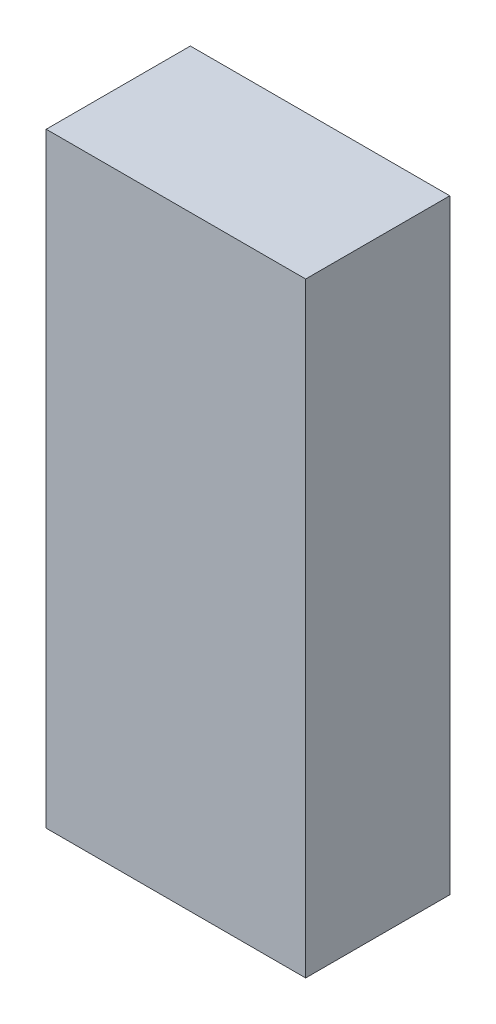
SolidWorks part; units mm, degrees
material "Copper"
ref_plane "Front Plane" through (0, 0, 0) normal (0, 0, 1) x (1, 0, 0)
ref_plane "Top Plane" through (0, 0, 0) normal (0, 1, 0) x (1, 0, 0)
ref_plane "Right Plane" through (0, 0, 0) normal (1, 0, 0) x (0, 0, -1)
sketch "Sketch1" plane through (0, 0, 0) normal (0, 0, 1) x (1, 0, 0)
  line L1 (-0.225, 0.525) -> (0.225, 0.525)
  line L2 (-0.225, 0.525) -> (-0.225, -0.525)
  line L3 (-0.225, -0.525) -> (0.225, -0.525)
  line L4 (0.225, 0.525) -> (0.225, -0.525)
  line L5 (0, -0.525) -> (0, 0.525) construction
  line L6 (-0.225, 0) -> (0.225, 0) construction
  point P0 (0, 0)
  dimension "D1" = 0.45
  dimension "D2" = 1.05
extrude "Boss-Extrude1" add sketch "Sketch1" along normal blind 0.25
